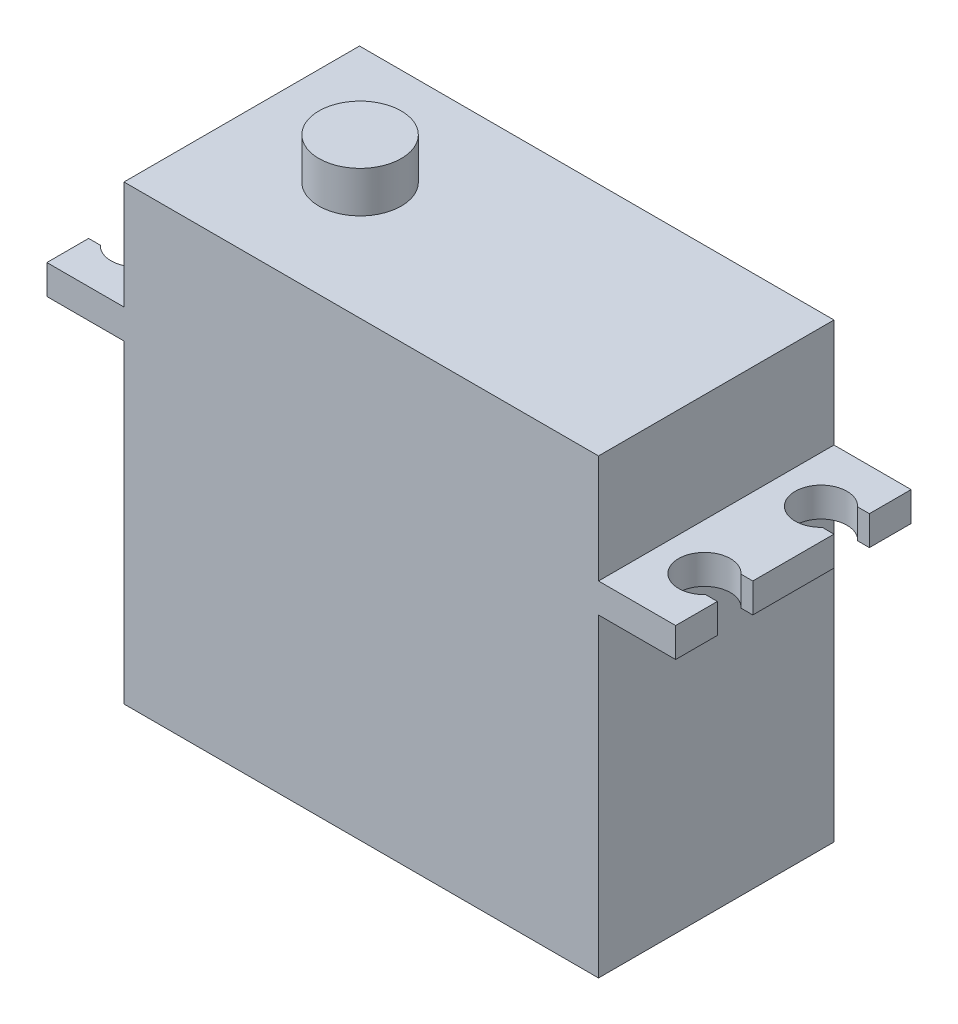
SolidWorks part; units mm, degrees
ref_plane "Front Plane" through (0, 0, 0) normal (0, 0, 1) x (1, 0, 0)
ref_plane "Top Plane" through (0, 0, 0) normal (0, 1, 0) x (1, 0, 0)
ref_plane "Right Plane" through (0, 0, 0) normal (1, 0, 0) x (0, 0, -1)
sketch "Sketch1" plane through (0, 0, 0) normal (0, 1, 0) x (1, 0, 0)
  line L1 (-20.15, 10) -> (20.15, 10)
  line L2 (-20.15, 10) -> (-20.15, -10)
  line L3 (-20.15, -10) -> (20.15, -10)
  line L4 (20.15, 10) -> (20.15, -10)
  line L5 (-20.15, 10) -> (20.15, -10) construction
  line L6 (-20.15, -10) -> (20.15, 10) construction
  point P0 (0, 0)
  dimension "D1" = 40.3
  dimension "D2" = 20
extrude "Boss-Extrude1" add sketch "Sketch1" along normal blind 38.4
sketch "Sketch3" plane through (0, 38.4, 0) normal (0, 1, 0) x (1, 0, 0)
  line L0 (20.15, 10) -> (-20.15, 10) construction
  line L1 (-26.7, 10) -> (26.7, 10)
  line L2 (-26.7, 10) -> (-26.7, 6.4552)
  line L3 (-26.7, -10) -> (26.7, -10)
  line L4 (26.7, 10) -> (26.7, 6.4552)
  line L5 (-26.7, 10) -> (26.7, -10) construction
  line L6 (-26.7, -10) -> (26.7, 10) construction
  line L7 (0, 0) -> (26.7, 0) construction
  line L8 (0, 0) -> (0, 10) construction
  line L9 (-26.7, -6.4552) -> (-26.7, -10)
  line L10 (-26.7, -3.4448) -> (-25.7045, -3.4448)
  line L12 (-26.7, -6.4552) -> (-25.7045, -6.4552)
  line L14 (-26.7, 3.4448) -> (-26.7, -3.4448)
  line L15 (26.7, 3.4448) -> (26.7, -3.4448)
  line L20 (-26.7, 3.4448) -> (-25.7045, 3.4448)
  line L22 (26.7, 6.4552) -> (25.7045, 6.4552)
  line L24 (26.7, 3.4448) -> (25.7045, 3.4448)
  line L28 (26.7, -3.4448) -> (25.7045, -3.4448)
  line L30 (26.7, -6.4552) -> (25.7045, -6.4552)
  line L32 (26.7, -6.4552) -> (26.7, -10)
  line L34 (-26.7, 6.4552) -> (-25.7045, 6.4552)
  arc A0 (-25.7045, -6.4552) -> (-25.7045, -3.4448) centre (-24.1, -4.95) ccw
  arc A1 (-25.7045, 3.4448) -> (-25.7045, 6.4552) centre (-24.1, 4.95) ccw
  arc A2 (25.7045, 6.4552) -> (25.7045, 3.4448) centre (24.1, 4.95) ccw
  arc A3 (25.7045, -3.4448) -> (25.7045, -6.4552) centre (24.1, -4.95) ccw
  point P0 (0, 0)
  point P16 (-30.3567, 4.95)
  point P20 (30.1246, 4.95)
  point P21 (-28.9651, -4.95)
  point P26 (0, 0)
  point P33 (32.0399, -4.95)
  point P38 (0, 0)
  point P39 (0, 0)
  point P40 (0, 0)
  dimension "D5" = 2.2
  dimension "D1" = 53.4
  dimension "D2" = 48.2
  dimension "D3" = 9.9
  dimension "D4" = 9.9
ref_plane "Plane1" through (0, 26.7, 0) normal (0, -1, 0) x (-1, 0, 0)
extrude "Boss-Extrude3" add sketch "Sketch3" along normal blind 2.5 from surface at -11.7 starting at plane "Plane1"
sketch "Sketch5" plane through (0, 38.4, 0) normal (0, 1, 0) x (1, 0, 0)
  line L0 (-26.7, -3.4448) -> (-26.7, 3.4448) construction
  line L1 (-20.15, -10) -> (-20.15, 10) construction
  circle A0 centre (-10.1, 0) radius 3.5
  point P4 (0, 0)
  point P7 (-20.15, 0)
  dimension "D2" = 7
  dimension "D1" = 16.6
extrude "Boss-Extrude4" add sketch "Sketch5" along normal blind 3.5
